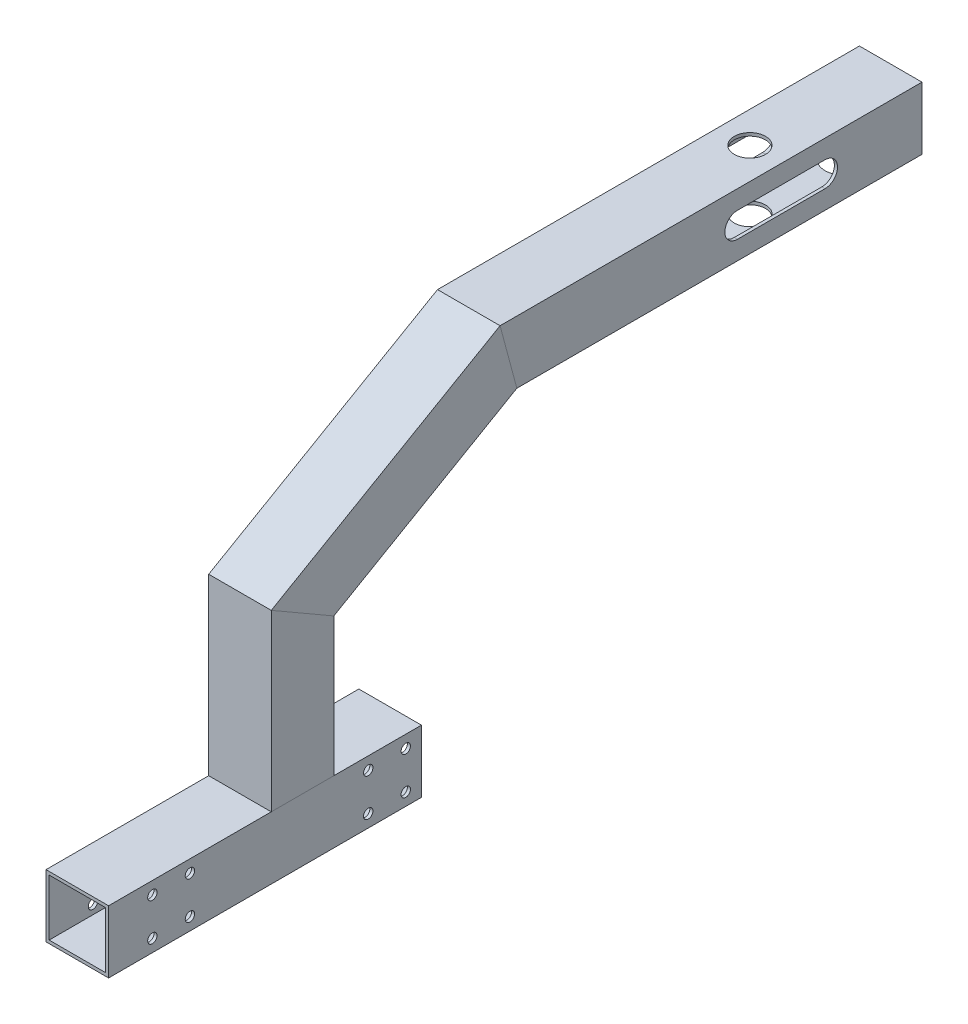
SolidWorks part; units mm, degrees
material "6063-O"
ref_plane "Front" through (0, 0, 0) normal (0, 0, 1) x (1, 0, 0)
ref_plane "Top" through (0, 0, 0) normal (0, 1, 0) x (1, 0, 0)
ref_plane "Right" through (0, 0, 0) normal (1, 0, 0) x (0, 0, -1)
sketch "草图1" plane through (0, 0, 0) normal (1, 0, 0) x (0, 0, -1)
  line L0 (0, 0) -> (62, 0) construction
  line L1 (62, 0) -> (62, 98) construction
  line L2 (62, 98) -> (260, 98) construction
  line L3 (0, 0) -> (100, 0)
  line L4 (62, 0) -> (62, 60)
  line L5 (62, 60) -> (127.8179, 98)
  line L6 (127.8179, 98) -> (260, 98)
  dimension "D1" = 62
  dimension "D2" = 98
  dimension "D3" = 198
  dimension "D4" = 100
  dimension "D5" = 60
  dimension "D6" = 60
other "铝管 20X20X1(14)"
ref_plane "基准面1" through (0, 0, 0) normal (0, 0, -1) x (0, 1, 0)
sketch "草图11" plane through (0, 0, 0) normal (0, 0, -1) x (0, 1, 0)
  line L1 (-10, -10) -> (10, -10)
  line L2 (-10, -10) -> (-10, 10)
  line L3 (-10, 10) -> (10, 10)
  line L4 (10, -10) -> (10, 10)
  line L5 (-10, -10) -> (10, 10) construction
  line L6 (-10, 10) -> (10, -10) construction
  line L7 (-9, -9) -> (9, -9)
  line L8 (-9, -9) -> (-9, 9)
  line L9 (-9, 9) -> (9, 9)
  line L10 (9, -9) -> (9, 9)
  line L11 (-9, -9) -> (9, 9) construction
  line L12 (-9, 9) -> (9, -9) construction
  point P0 (0, 0)
  point P6 (0, 0)
  point P11 (0, 0)
  dimension "D1" = 20
  dimension "D2" = 20
  dimension "D3" = 18
  dimension "D4" = 18
sketch "草图12" plane through (10, 0, 0) normal (1, 0, 0) x (0, 0, -1)
  line L0 (0, 0) -> (100, 0) construction
  line L1 (0, 10) -> (0, -10) construction
  line L2 (100, 10) -> (100, -10) construction
  circle A0 centre (14, 6) radius 1.5
  circle A1 centre (14, -6) radius 1.5
  circle A2 centre (26, 6) radius 1.5
  circle A3 centre (26, -6) radius 1.5
  circle A4 centre (83, 6) radius 1.5
  circle A5 centre (83, -6) radius 1.5
  circle A6 centre (95, 6) radius 1.5
  circle A7 centre (95, -6) radius 1.5
  dimension "D1" = 3
  dimension "D2" = 3
  dimension "D3" = 12
  dimension "D4" = 14
  dimension "D5" = 2
  dimension "D6" = 2
extrude "切除-拉伸1" cut sketch "草图12" against normal through all
sketch "草图13" plane through (0, 88, 0) normal (0, -1, 0) x (1, 0, 0)
  line L0 (0, 0) -> (0, -260) construction
  line L1 (10, 0) -> (-10, 0) construction
  line L2 (10, -260) -> (-10, -260) construction
  circle A0 centre (0, -215) radius 5
  dimension "D1" = 10
  dimension "D2" = 215
extrude "切除-拉伸2" cut sketch "草图13" against normal through all
sketch "草图14" plane through (10, 0, 0) normal (1, 0, 0) x (0, 0, -1)
  line L0 (201, 98) -> (229, 98) construction
  line L1 (201, 102) -> (229, 102)
  line L2 (201, 94) -> (229, 94)
  line L3 (0, 10) -> (0, -10) construction
  line L4 (260, 108) -> (125.1384, 108) construction
  arc A0 (201, 102) -> (201, 94) centre (201, 98) ccw
  arc A1 (229, 94) -> (229, 102) centre (229, 98) ccw
  point P2 (215, 98)
  dimension "D4" = 28
  dimension "D1" = 215
  dimension "D2" = 10
  dimension "D3" = 8
extrude "切除-拉伸3" cut sketch "草图14" against normal through all
sketch "草图15" plane through (0, 88, 0) normal (0, -1, 0) x (1, 0, 0)
  line L0 (0, -260) -> (0, -226.8111) construction
  line L1 (10, -260) -> (-10, -260) construction
  circle A0 centre (0, -245) radius 6
  dimension "D1" = 12
  dimension "D2" = 15
extrude "切除-拉伸4" cut sketch "草图15" against normal up to next (1 mm away)
sketch "草图16" plane through (0, 88, 0) normal (0, -1, 0) x (1, 0, 0)
  line L0 (10, -260) -> (-10, -260) construction
  line L1 (10, -260) -> (10, -130.4974) construction
  circle A0 centre (6, -254) radius 1.5
  dimension "D1" = 3
  dimension "D2" = 6
  dimension "D3" = 4
extrude "切除-拉伸5" cut sketch "草图16" against normal up to next (1 mm away)
